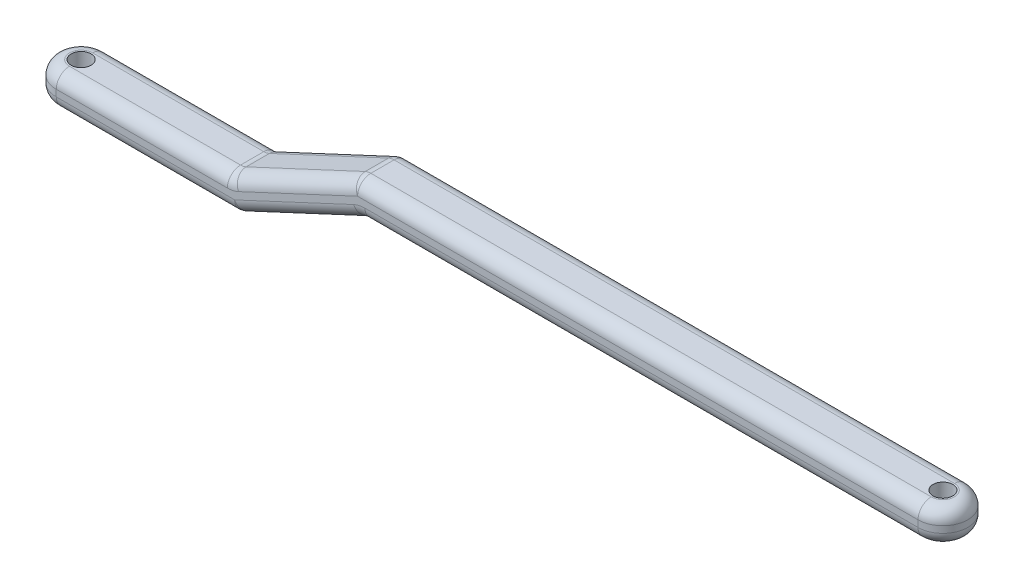
SolidWorks part; units mm, degrees
material "ABS PC"
ref_plane "Alzado" through (0, 0, 0) normal (1, 0, 0) x (0, 1, 0)
ref_plane "Planta" through (0, 0, 0) normal (0, 0, 1) x (0, 1, 0)
ref_plane "Vista lateral" through (0, 0, 0) normal (0, 1, 0) x (-1, 0, 0)
sketch "Croquis1" plane through (0, 0, 0) normal (0, 1, 0) x (-1, 0, 0)
  line L0 (0, 0) -> (260, 0) construction
  line L1 (0, 0) -> (260, 0) construction
  line L2 (0, 7.5) -> (260, 7.5)
  line L3 (0, -7.5) -> (260, -7.5)
  circle A0 centre (0, 0) radius 3
  circle A1 centre (260, 0) radius 3
  arc A2 (0, 7.5) -> (0, -7.5) centre (0, 0) ccw
  arc A3 (260, -7.5) -> (260, 7.5) centre (260, 0) ccw
  point P5 (130, 0)
  dimension "D1" = 6
  dimension "D2" = 15
  dimension "D3" = 260
extrude "Saliente-Extruir1" add sketch "Croquis1" along normal mid plane 27.5
sketch "Croquis3" plane through (0, 0, 0) normal (0, 0, 1) x (0, 1, 0)
  line L2 (13.75, 267.5) -> (-13.75, 267.5) construction
  line L3 (13.75, 0) -> (13.75, 260) construction
  line L4 (13.75, 169.9711) -> (13.75, -7.5)
  line L5 (13.75, -7.5) -> (3.75, -7.5)
  line L6 (-13.75, -7.5) -> (13.75, -7.5) construction
  line L7 (3.75, -7.5) -> (3.75, 167.7542)
  line L8 (3.75, 167.7542) -> (-13.75, 205.2831)
  line L9 (-13.75, 0) -> (-13.75, 260) construction
  line L10 (-3.75, 267.5) -> (-13.75, 267.5)
  line L11 (-13.75, 267.5) -> (-13.75, 205.2831)
  line L12 (-3.75, 267.5) -> (-3.75, 207.5)
  line L13 (-3.75, 207.5) -> (13.75, 169.9711)
  line L14 (-3.75, 207.5) -> (-12.8131, 203.2738) construction
  dimension "D1" = 10
  dimension "D2" = 60
  dimension "D3" = 25
extrude "Cortar-Extruir1" cut sketch "Croquis3" against normal through all both and the other way through all flip side to cut
fillet "Redondeo5" radius 4 20 edges at (-232.6415, -13.75, 7.5) (-267.5, -13.75, 0) (-232.6415, -13.75, -7.5) (-84.9856, 13.75, 7.5) (-84.9856, 13.75, -7.5) (7.5, 13.75, 0) (-186.5186, -5, 7.5) (-83.8771, 3.75, 7.5) (-233.75, -3.75, -7.5) (-167.7542, 3.75, 0) (-205.2831, -13.75, 0) (-207.5, -3.75, 0) (-169.9711, 13.75, 0) (-83.8771, 3.75, -7.5) (-186.5186, -5, -7.5) (-188.7356, 5, -7.5) (-233.75, -3.75, 7.5) (-188.7356, 5, 7.5) (7.5, 3.75, 0) (-267.5, -3.75, 0)
equation "\"L2\"= 260"
equation "\"ancho\"= 15"
equation "\"esp\"= 10"
equation "\"agujeros\"= 6"
equation "\"D1@Croquis1\"=\"agujeros\""
equation "\"D2@Croquis1\"=\"ancho\""
equation "\"D3@Croquis1\"=\"L2\""
equation "\"D1@Saliente-Extruir1\"=\"esp\"+17.5"
equation "\"D1@Croquis3\"=\"esp\""
